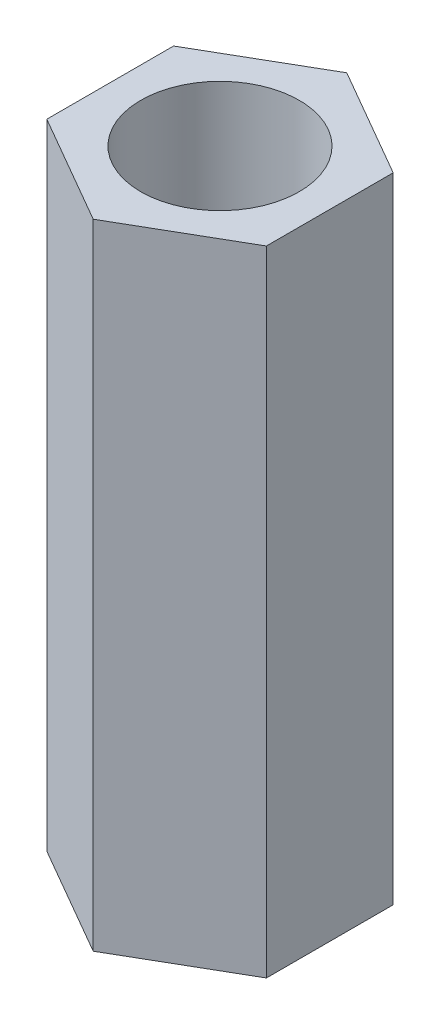
SolidWorks part; units mm, degrees
material "黄铜"
ref_plane "前视基准面" through (0, 0, 0) normal (0, 0, 1) x (1, 0, 0)
ref_plane "上视基准面" through (0, 0, 0) normal (0, 1, 0) x (1, 0, 0)
ref_plane "右视基准面" through (0, 0, 0) normal (1, 0, 0) x (0, 0, -1)
other "Configuration Table"
sketch "草图1" plane through (0, 0, 0) normal (0, 1, 0) x (1, 0, 0)
  line L1 (0, 2) -> (-1.7321, 1)
  line L2 (-1.7321, 1) -> (-1.7321, -1)
  line L3 (-1.7321, -1) -> (0, -2)
  line L4 (0, -2) -> (1.7321, -1)
  line L5 (1.7321, -1) -> (1.7321, 1)
  line L6 (1.7321, 1) -> (0, 2)
  circle A0 centre (0, 0) radius 1.25
  circle A1 centre (0, 0) radius 1.7321 construction
  dimension "D1" = 2.5
  dimension "D2" = 4
extrude "凸台-拉伸1" add sketch "草图1" along normal blind 10
